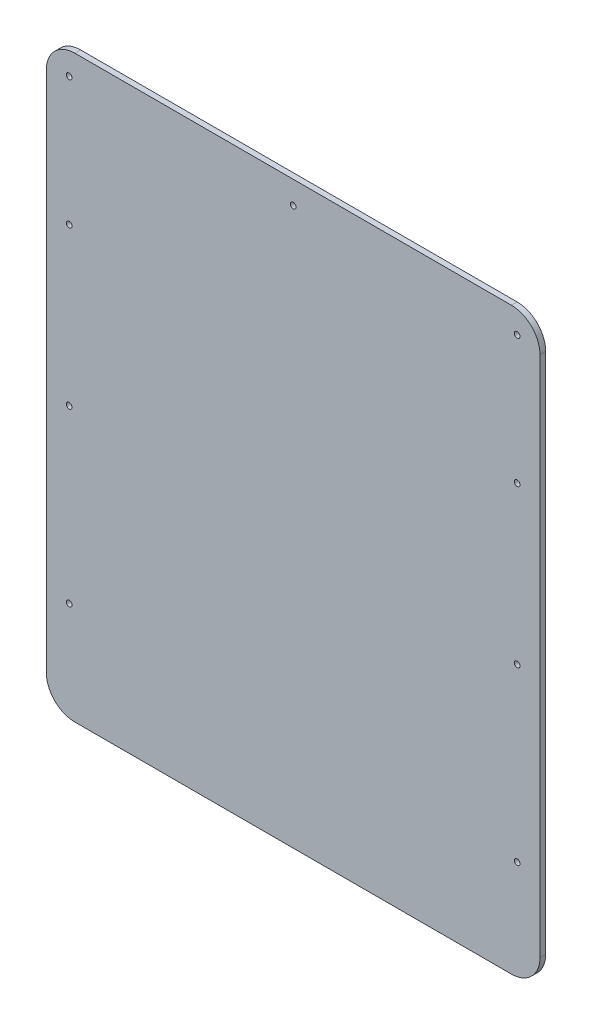
SolidWorks part; units mm, degrees
material "Acrylic (Medium-high impact)"
ref_plane "Front Plane" through (0, 0, 0) normal (0, 0, 1) x (1, 0, 0)
ref_plane "Top Plane" through (0, 0, 0) normal (0, 1, 0) x (1, 0, 0)
ref_plane "Right Plane" through (0, 0, 0) normal (1, 0, 0) x (0, 0, -1)
sketch "Sketch1" plane through (0, 0, 0) normal (0, 0, 1) x (1, 0, 0)
  line L0 (0, -55) -> (0, 55) construction
  line L1 (-153, 203) -> (153, 203)
  line L2 (-173, 183) -> (-173, -183)
  line L3 (-153, -203) -> (153, -203)
  line L4 (173, 183) -> (173, -183)
  circle A0 centre (-157, 187) radius 2
  circle A1 centre (-157, 97) radius 2
  circle A2 centre (-157, -13) radius 2
  circle A3 centre (-157, -133) radius 2
  circle A4 centre (157, -133) radius 2
  circle A5 centre (157, -13) radius 2
  circle A6 centre (157, 97) radius 2
  circle A7 centre (157, 187) radius 2
  circle A8 centre (0, 187) radius 2
  arc A9 (-153, -203) -> (-173, -183) centre (-153, -183) cw
  arc A10 (173, -183) -> (153, -203) centre (153, -183) cw
  arc A11 (173, 183) -> (153, 203) centre (153, 183) ccw
  arc A12 (-173, 183) -> (-153, 203) centre (-153, 183) cw
  point P27 (-173, -203)
  point P34 (-173, 203)
  dimension "D5" = 4
  dimension "D6" = 4
  dimension "D7" = 4
  dimension "D8" = 4
  dimension "D9" = 16
  dimension "D10" = 16
  dimension "D11" = 90
  dimension "D12" = 190
  dimension "D13" = 70
  dimension "D14" = 4
  dimension "D15" = 173
  dimension "D16" = 20
  dimension "D1" = 406
  dimension "D2" = 346
  dimension "D3" = 173
  dimension "D4" = 203
extrude "Boss-Extrude1" add sketch "Sketch1" along normal blind 4 contours L4 L1 L2 L3 A8 A6 A4 A3 A2 A1 A0 A5 A7
